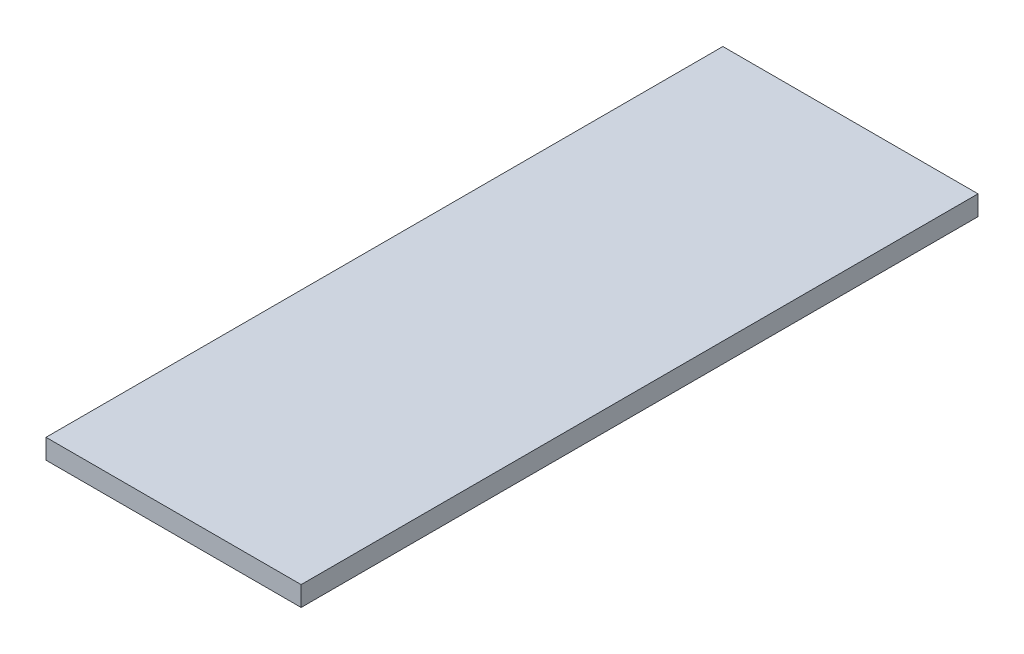
SolidWorks part; units mm, degrees
ref_plane "Front Plane" through (0, 0, 0) normal (0, 0, 1) x (1, 0, 0)
ref_plane "Top Plane" through (0, 0, 0) normal (0, 1, 0) x (1, 0, 0)
ref_plane "Right Plane" through (0, 0, 0) normal (1, 0, 0) x (0, 0, -1)
sketch "Sketch1" plane through (0, 0, 0) normal (0, 1, 0) x (1, 0, 0)
  line L1 (-122.5, 325) -> (122.5, 325)
  line L2 (-122.5, 325) -> (-122.5, -325)
  line L3 (-122.5, -325) -> (122.5, -325)
  line L4 (122.5, 325) -> (122.5, -325)
  line L5 (0, -325) -> (0, 325) construction
  line L6 (-122.5, 0) -> (122.5, 0) construction
  point P0 (0, 0)
  dimension "D1" = 650
  dimension "D2" = 245
extrude "Boss-Extrude1" add sketch "Sketch1" along normal blind 19.05
